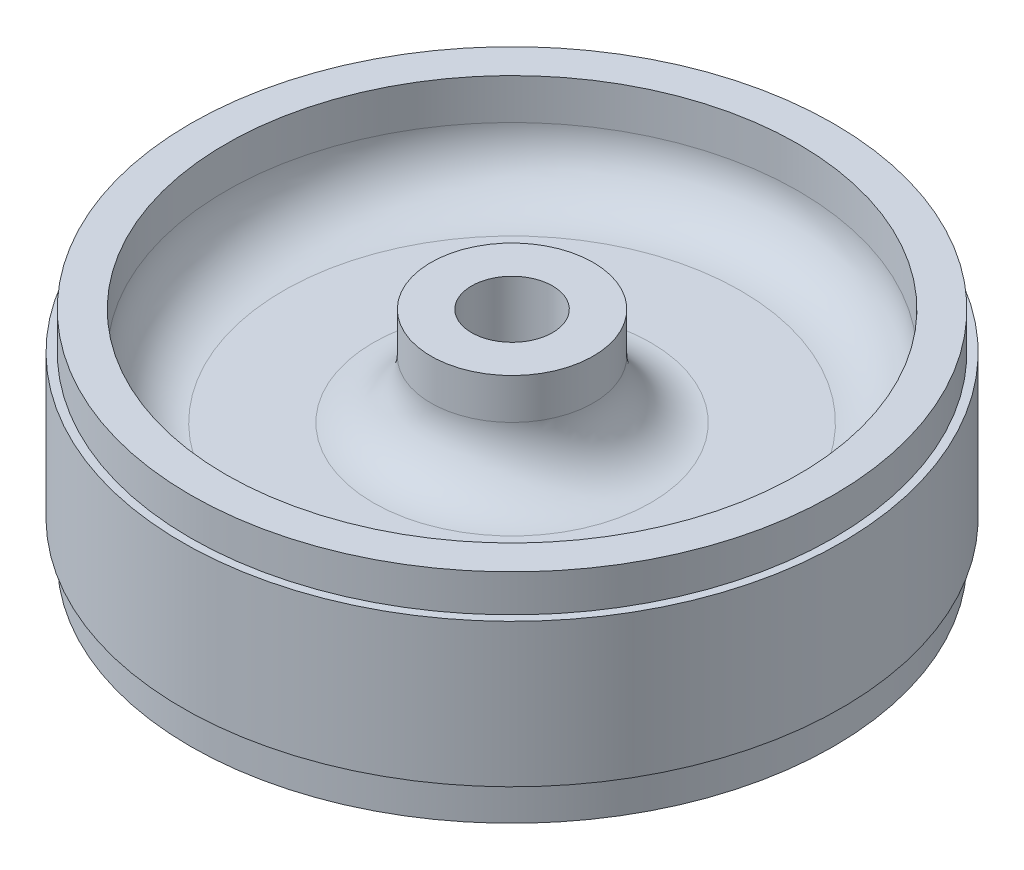
SolidWorks part; units mm, degrees
ref_plane "Front Plane" through (0, 0, 0) normal (0, 0, 1) x (1, 0, 0)
ref_plane "Top Plane" through (0, 0, 0) normal (0, 1, 0) x (1, 0, 0)
ref_plane "Right Plane" through (0, 0, 0) normal (1, 0, 0) x (0, 0, -1)
sketch "Sketch1" plane through (0, 0, 0) normal (0, 0, 1) x (1, 0, 0)
  line L0 (0, 0) -> (0, 62.4029) construction
  line L1 (-9.7409, 26.1853) -> (-9.7409, -26.1853)
  line L2 (-9.7409, 26.1853) -> (-19.5223, 26.1853)
  line L3 (-19.5223, 26.1853) -> (-19.5223, 16.4092)
  line L4 (-33.3727, 2.5588) -> (-55.0007, 2.5588)
  line L5 (-68.8511, 16.4092) -> (-68.8511, 26.1853)
  line L6 (-77.3516, 17.3736) -> (-77.3516, 17.2331)
  line L7 (-77.3516, 17.2331) -> (-79.265, 17.2331)
  line L8 (-79.265, 17.2331) -> (-79.265, -17.2331)
  line L9 (0, 0) -> (13.0075, 0) construction
  line L10 (-77.3516, -17.2331) -> (-79.265, -17.2331)
  line L11 (-77.3516, -17.3736) -> (-77.3516, -17.2331)
  line L12 (-68.8511, -16.4092) -> (-68.8511, -26.1853)
  line L13 (-33.3727, -2.5588) -> (-55.0007, -2.5588)
  line L14 (-19.5223, -26.1853) -> (-19.5223, -16.4092)
  line L15 (-9.7409, -26.1853) -> (-19.5223, -26.1853)
  line L16 (-68.8511, 26.1853) -> (-77.3516, 26.1853)
  line L17 (-77.3516, 26.1853) -> (-77.3516, 17.3736)
  line L18 (-77.3516, -26.1853) -> (-77.3516, -17.3736)
  line L19 (-68.8511, -26.1853) -> (-77.3516, -26.1853)
  arc A0 (-19.5223, 16.4092) -> (-33.3727, 2.5588) centre (-33.3727, 16.4092) cw
  arc A1 (-55.0007, 2.5588) -> (-68.8511, 16.4092) centre (-55.0007, 16.4092) cw
  arc A2 (-55.0007, -2.5588) -> (-68.8511, -16.4092) centre (-55.0007, -16.4092) ccw
  arc A3 (-19.5223, -16.4092) -> (-33.3727, -2.5588) centre (-33.3727, -16.4092) ccw
  point P24 (-79.265, 0)
  point P28 (-9.7409, 0)
revolve "Revolve1" add sketch "Sketch1" angle 360 about L0
